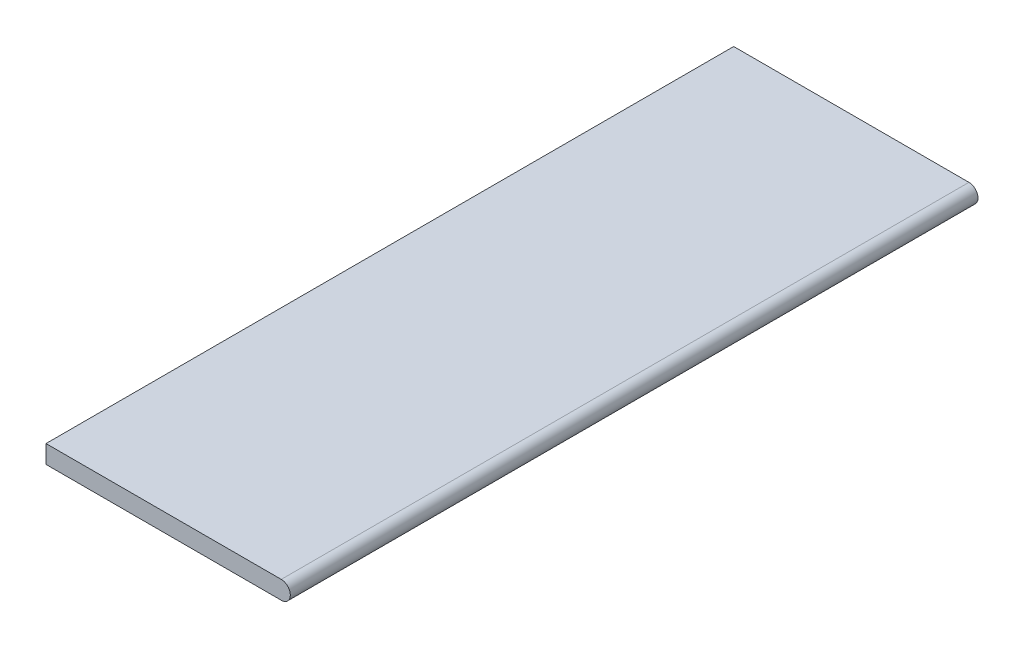
SolidWorks part; units mm, degrees
ref_plane "Спереди" through (0, 0, 0) normal (0, 0, 1) x (1, 0, 0)
ref_plane "Сверху" through (0, 0, 0) normal (0, 1, 0) x (1, 0, 0)
ref_plane "Справа" through (0, 0, 0) normal (1, 0, 0) x (0, 0, -1)
other "Configuration Table"
sketch "Эскиз1" plane through (0, 0, 0) normal (0, 1, 0) x (1, 0, 0)
  line L1 (-32.5, 95) -> (32.5, 95)
  line L2 (-32.5, 95) -> (-32.5, -95)
  line L3 (-32.5, -95) -> (32.5, -95)
  line L4 (32.5, 95) -> (32.5, -95)
  line L5 (-32.5, 95) -> (32.5, -95) construction
  line L6 (-32.5, -95) -> (32.5, 95) construction
  point P0 (0, 0)
  dimension "D1" = 65
  dimension "D2" = 190
extrude "Бобышка-Вытянуть1" add sketch "Эскиз1" along normal blind 5
sketch "Эскиз2" plane through (0, 0, 0) normal (0, 0, 1) x (1, 0, 0)
  line L0 (32.5, 5) -> (32.5, 0) construction
  line L1 (32.5, 5) -> (32.5, 0)
  line L2 (-32.5, 0) -> (32.5, 0) construction
  arc A0 (32.5, 5) -> (32.5, 0) centre (32.5, 2.5) cw
extrude "Бобышка-Вытянуть2" add sketch "Эскиз2" along normal through all and the other way through all contours A0 L1
